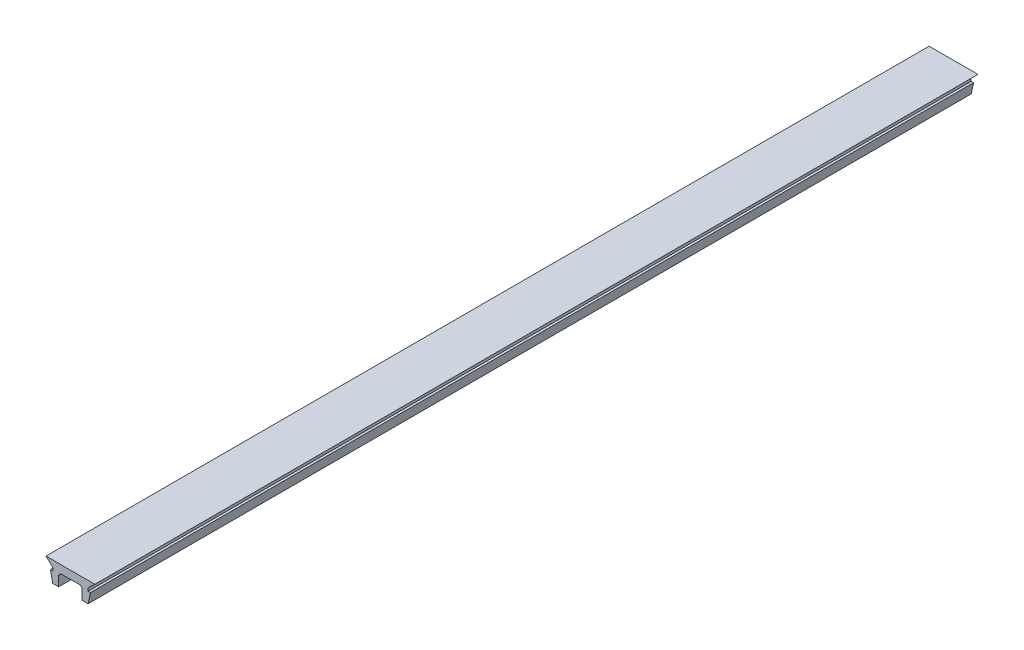
SolidWorks part; units mm, degrees
ref_plane "Front Plane" through (0, 0, 0) normal (0, 0, 1) x (1, 0, 0)
ref_plane "Top Plane" through (0, 0, 0) normal (0, 1, 0) x (1, 0, 0)
ref_plane "Right Plane" through (0, 0, 0) normal (1, 0, 0) x (0, 0, -1)
sketch "Sketch1" plane through (0, 0, 0) normal (0, 0, 1) x (1, 0, 0)
  line L0 (6, 0) -> (6.4, 1.85)
  line L1 (0, 0) -> (1, 0)
  line L2 (0, 1.85) -> (0, 2.35)
  line L3 (0, 3.45) -> (6, 3.45)
  line L4 (6, 1.85) -> (6, 2.35)
  line L5 (6.4, 1.85) -> (6, 1.85)
  line L6 (-0.4, 1.85) -> (0, 0)
  line L7 (0, 1.85) -> (-0.4, 1.85)
  line L8 (5, 0) -> (6, 0)
  line L10 (1, 0) -> (1, 1.6)
  line L11 (1.5, 2.1) -> (4.5, 2.1)
  line L12 (5, 0) -> (5, 1.6)
  line L13 (6, 3.45) -> (7.15, 3.45)
  line L14 (7.15, 3.45) -> (6, 2.35)
  line L16 (0, 2.35) -> (-1.15, 3.45)
  line L17 (-1.15, 3.45) -> (0, 3.45)
  arc A0 (4.5, 2.1) -> (5, 1.6) centre (4.5, 1.6) cw
  arc A1 (1.5, 2.1) -> (1, 1.6) centre (1.5, 1.6) ccw
  point P21 (0, 0)
  dimension "D9" = 0.5
  dimension "D1" = 6
  dimension "D2" = 1.6
  dimension "D3" = 1.85
  dimension "D4" = 0.4
  dimension "D5" = 0.4
  dimension "D7" = 1
  dimension "D8" = 1
  dimension "D10" = 8.3
  dimension "D11" = 0.5
extrude "Boss-Extrude1" add sketch "Sketch1" along normal blind 150
